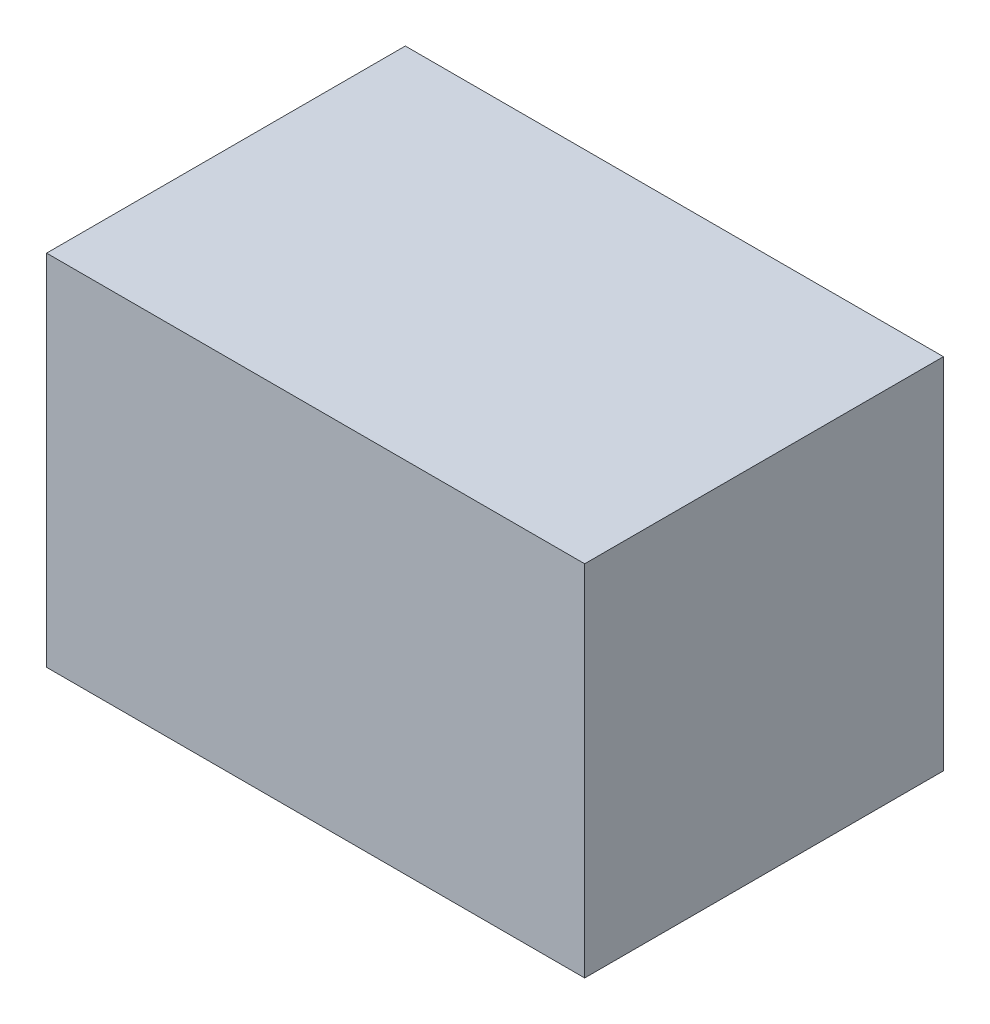
SolidWorks part; units mm, degrees
ref_plane "Front Plane" through (0, 0, 0) normal (0, 0, 1) x (1, 0, 0)
ref_plane "Top Plane" through (0, 0, 0) normal (0, 1, 0) x (1, 0, 0)
ref_plane "Right Plane" through (0, 0, 0) normal (1, 0, 0) x (0, 0, -1)
sketch "Sketch1" plane through (0, 0, 0) normal (0, 1, 0) x (1, 0, 0)
  line L1 (0, 0) -> (60, 0)
  line L2 (0, 0) -> (0, 40)
  line L3 (0, 40) -> (60, 40)
  line L4 (60, 0) -> (60, 40)
  dimension "D1" = 60
  dimension "D2" = 40
extrude "Boss-Extrude1" add sketch "Sketch1" along normal blind 40
